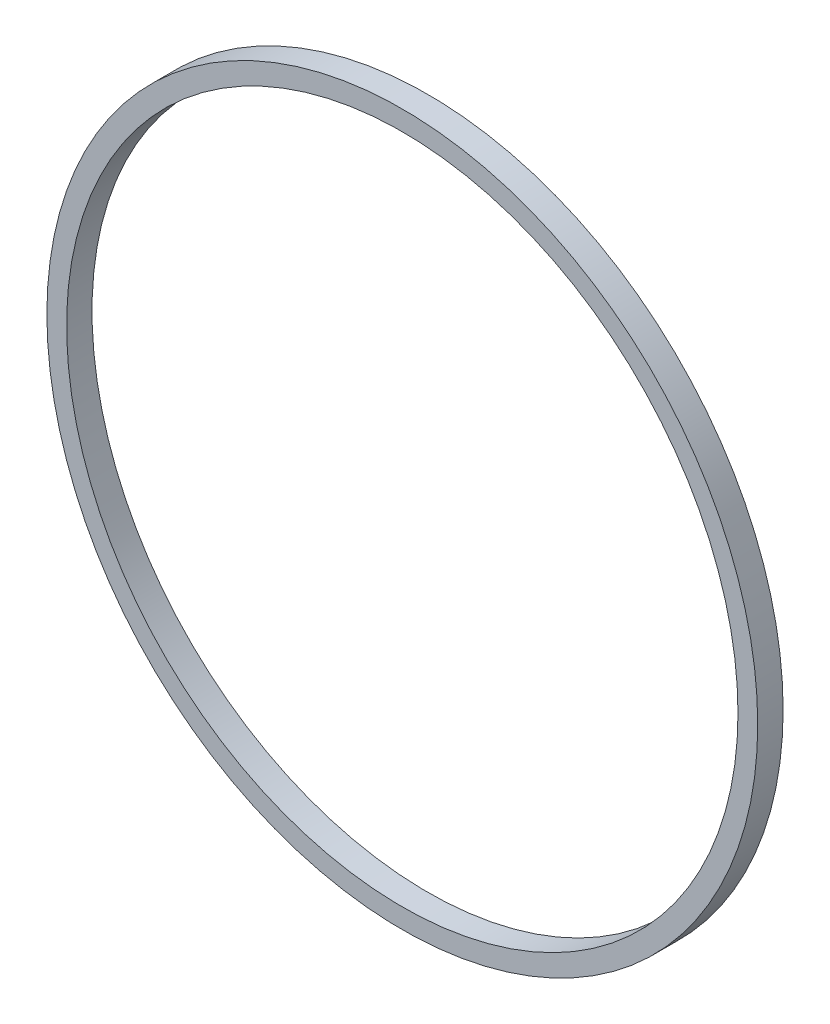
SolidWorks part; units mm, degrees
ref_plane "Front Plane" through (0, 0, 0) normal (0, 0, 1) x (1, 0, 0)
ref_plane "Top Plane" through (0, 0, 0) normal (0, 1, 0) x (1, 0, 0)
ref_plane "Right Plane" through (0, 0, 0) normal (1, 0, 0) x (0, 0, -1)
sketch "Sketch1" plane through (0, 0, 0) normal (0, 0, 1) x (1, 0, 0)
  arc B0 (164.1468, 89.4159) -> (164.1468, 79.1202) centre (165.1773, 84.268) ccw
  arc B1 (164.1468, 89.4159) -> (27.5816, 168.2619) centre (16.0718, -9.3656) ccw
  arc B2 (18.6652, 163.114) -> (27.5816, 168.2619) centre (22.6081, 166.5804) ccw
  arc B3 (18.6652, 163.114) -> (18.6652, 5.4221) centre (178.25, 84.268) ccw
  arc B4 (27.5816, 0.2742) -> (18.6652, 5.4221) centre (22.6081, 1.9557) ccw
  arc B5 (27.5816, 0.2742) -> (164.1468, 79.1202) centre (16.0718, 177.9017) ccw
  arc B6 (18.6136, 163.5731) -> (18.6136, 4.963) centre (178.25, 84.268) ccw
  arc B7 (27.2098, 0) -> (164.5701, 79.305) centre (16.0718, 177.9017) ccw
  arc B8 (164.5701, 89.231) -> (27.2098, 168.5361) centre (16.0718, -9.3656) ccw
  circle B9 centre (70.1312, 84.268) radius 63
  circle B10 centre (70.1312, 84.268) radius 59.5
  circle B11 centre (70.1312, 84.268) radius 58.5
  circle B12 centre (70.1312, 84.268) radius 55
sketch_block_instance "Seals Block-1"
sketch_block "Seals Block"
extrude "Boss-Extrude2" add sketch "Sketch1" along normal blind 4.5 contours B9 B10
